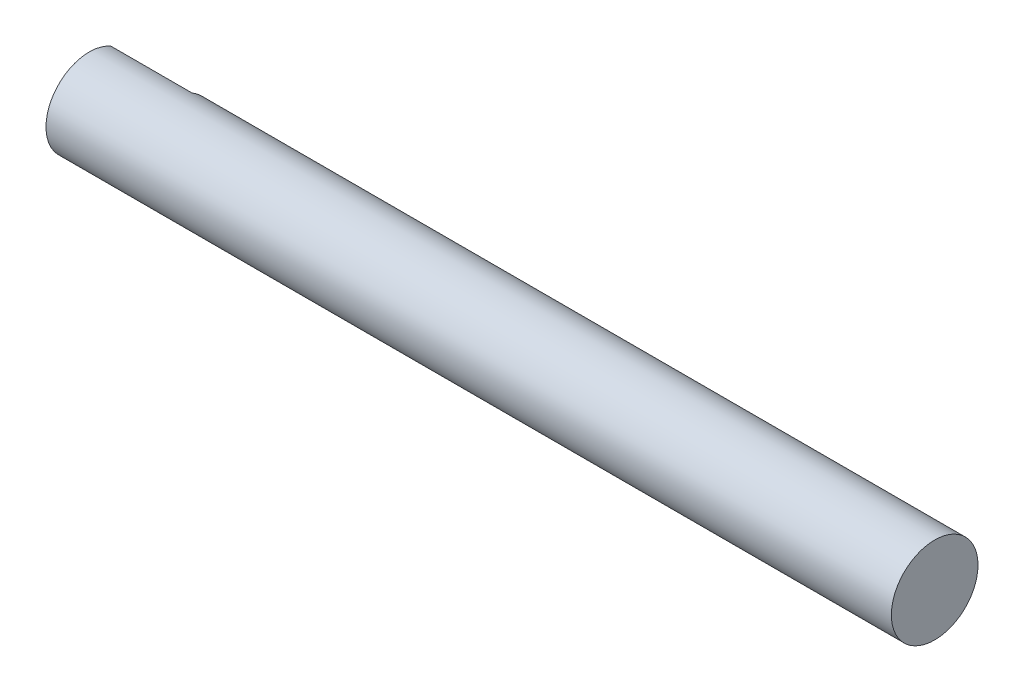
SolidWorks part; units mm, degrees
ref_plane "Front Plane" through (0, 0, 0) normal (0, 0, 1) x (1, 0, 0)
ref_plane "Top Plane" through (0, 0, 0) normal (0, 1, 0) x (1, 0, 0)
ref_plane "Right Plane" through (0, 0, 0) normal (1, 0, 0) x (0, 0, -1)
sketch "Sketch1" plane through (0, 0, 0) normal (1, 0, 0) x (0, 0, -1)
  line L0 (1.985, 3.467) -> (1.985, -3.467)
  line L1 (-3.995, -8) -> (1.985, -8) construction
  line L2 (-3.995, -8) -> (-3.995, 0) construction
  line L4 (1.985, -8) -> (1.985, 3.467) construction
  arc A0 (1.985, 3.467) -> (1.985, -3.467) centre (0, 0) ccw
  dimension "D1" = 7.99
  dimension "D2" = 5.98
  dimension "D3" = 8
extrude "Boss-Extrude1" add sketch "Sketch1" along normal blind 7.5
sketch "Sketch2" plane through (7.5, 0, 0) normal (1, 0, 0) x (0, 0, -1)
  circle A0 centre (0, 0) radius 3.995
  dimension "D1" = 7.99
extrude "Boss-Extrude2" add sketch "Sketch2" along normal blind 70.446
